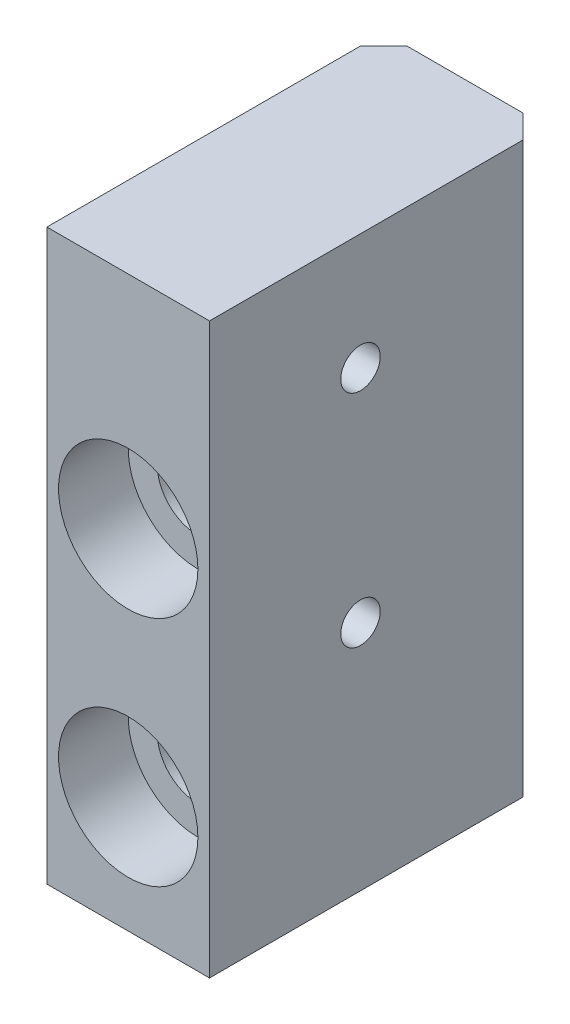
SolidWorks part; units mm, degrees
material "3D printed plastic"
ref_plane "Front Plane" through (0, 0, 0) normal (0, 0, 1) x (1, 0, 0)
ref_plane "Top Plane" through (0, 0, 0) normal (0, 1, 0) x (1, 0, 0)
ref_plane "Right Plane" through (0, 0, 0) normal (1, 0, 0) x (0, 0, -1)
sketch "Sketch1" plane through (0, 0, 0) normal (1, 0, 0) x (0, 0, -1)
  line L0 (0, 4.75) -> (0, -4.75) construction
  line L1 (-6.5, 9.75) -> (8, 9.75)
  line L2 (-6.5, 9.75) -> (-6.5, -14.75)
  line L3 (-6.5, -14.75) -> (8, -14.75)
  line L4 (8, 9.75) -> (8, -14.75)
  circle A0 centre (0, 4.75) radius 0.85
  circle A1 centre (0, -4.75) radius 0.85
  dimension "D1" = 9.5
  dimension "D2" = 1.7
  dimension "D4" = 8
  dimension "D5" = 5
  dimension "D6" = 10
  dimension "D3" = 6.5
extrude "Boss-Extrude1" add sketch "Sketch1" along normal blind 7
chamfer "Chamfer1" distance 1 angle 45 2 edges at (7, -2.5, -8) (0, -2.5, -8)
sketch "Sketch2" plane through (0, 0, 6.5) normal (0, 0, 1) x (1, 0, 0)
  line L0 (3.5, 0.25) -> (3.5, -9.75) construction
  line L1 (3.5, -4.75) -> (0, -4.75) construction
  line L2 (0, 9.75) -> (0, -14.75) construction
  line L3 (3.5, -4.75) -> (7, -4.75) construction
  line L4 (7, 9.75) -> (7, -14.75) construction
  line L5 (0, -3.9) -> (0, -5.6) construction
  circle A0 centre (3.5, 0.25) radius 1.75
  circle A1 centre (3.5, -9.75) radius 1.75
  dimension "D1" = 10
  dimension "D2" = 3.5
extrude "Cut-Extrude1" cut sketch "Sketch2" against normal through all
sketch "Sketch3" plane through (0, 0, 6.5) normal (0, 0, 1) x (1, 0, 0)
  circle A0 centre (3.5, 0.25) radius 3
  circle A1 centre (3.5, -9.75) radius 3
  dimension "D1" = 6
extrude "Cut-Extrude2" cut sketch "Sketch3" against normal blind 3
